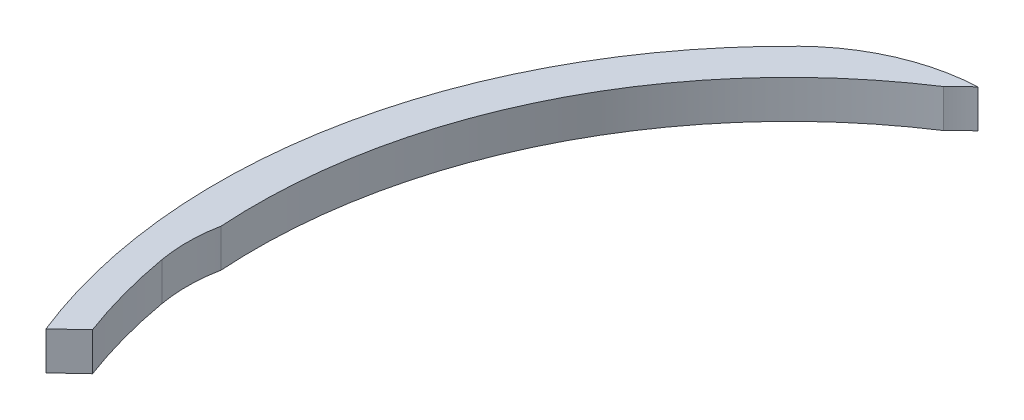
SolidWorks part; units mm, degrees
ref_plane "Plan de face" through (0, 0, 0) normal (0, 0, 1) x (1, 0, 0)
ref_plane "Plan de dessus" through (0, 0, 0) normal (0, 1, 0) x (1, 0, 0)
ref_plane "Plan de droite" through (0, 0, 0) normal (1, 0, 0) x (0, 0, -1)
sketch "Esquisse1" plane through (0, 0, 0) normal (0, 1, 0) x (1, 0, 0)
  line L0 (-85.9865, -39.2209) -> (-82.8365, -36.2747)
  line L3 (-9.4508, 5.6286) -> (-14.9085, -3.5351) construction
  line L5 (3.3105, -15.9387) -> (9.4508, -5.6286) construction
  line L12 (0, 0) -> (-80, 0) construction
  line L13 (-64.4502, -24.994) -> (-51.2217, 24.3754) construction
  line L14 (-65, 0) -> (-64.4502, -24.994) construction
  arc A0 (-44.8834, -16.4709) -> (3.3105, -15.9387) centre (-21.2415, 25) ccw construction
  arc A1 (-20.1052, -3.4627) -> (-14.9085, -3.5351) centre (-17.486, -2) ccw construction
  arc A2 (-20.1052, -3.4627) -> (-29.494, 14.405) centre (325.5264, 189.5538) cw construction
  arc A3 (-13.5326, 17.4331) -> (-23.8264, -39.4451) centre (-16.3245, -11.4322) ccw construction
  arc A4 (-40.7805, 12.1878) -> (-49.9076, -6.124) centre (-16.3245, -11.4322) ccw construction
  arc A5 (-13.0513, 22.4098) -> (-25.1198, -44.2749) centre (-16.3245, -11.4322) ccw construction
  arc A6 (-54.6669, 47.1327) -> (-86.1705, -16.0732) centre (-16.3245, -11.4322) ccw
  arc A7 (-86.1705, -16.0732) -> (-86.2446, -23.7683) centre (-65.564, -20.1196) ccw
  arc A8 (-55.3204, 19.8618) -> (-29.494, 14.405) centre (-39.0306, 33.1147) ccw
  arc A9 (-86.2446, -23.7683) -> (-82.8365, -36.2747) centre (-16.3245, -11.4322) ccw
  arc A36 (-51.2217, 24.3754) -> (-64.4502, -24.994) centre (-16.3245, -11.4322) ccw construction
  arc A37 (-68.6703, 42.2792) -> (-85.9865, -39.2209) centre (-16.3245, -11.4322) ccw
  arc A41 (9.4508, -5.6286) -> (-9.4508, 5.6286) centre (0, 0) ccw construction
  arc A42 (-16.402, 38.5677) -> (-47.4539, -50.5598) centre (-16.3245, -11.4322) ccw construction
  arc A43 (-52.3505, 49.3499) -> (-54.6669, 47.1327) centre (-39.0306, 33.1147) ccw
  arc A44 (-52.3505, 49.3499) -> (-68.6703, 42.2792) centre (-51.2217, 24.3754) ccw
  arc A45 (-44.8834, -16.4709) -> (-64.7884, 0.8661) centre (-65.564, -20.1196) ccw
  point P78 (-56.6847, 2.6915)
  point P85 (-65, 0)
  dimension "D4" = 25
  dimension "D5" = 12
  dimension "D6" = 21
  dimension "D7" = 5
  dimension "D8" = 25
  dimension "D9" = 5
  dimension "D10" = 3
  dimension "D11" = 17.6
  dimension "D18" = 80
  dimension "D20" = 75
  dimension "D26" = 11
  dimension "D13" = 50
  dimension "D14" = 21
  dimension "D12" = 2
  dimension "D22" = 25
  dimension "D23" = 75
  dimension "D24" = 28
  dimension "D25" = 15
  dimension "D30" = 15
  dimension "D32" = 5
extrude "Boss.-Extru.1" add sketch "Esquisse1" along normal blind 5 contours A43 A44 A37 L0 A7 A6
